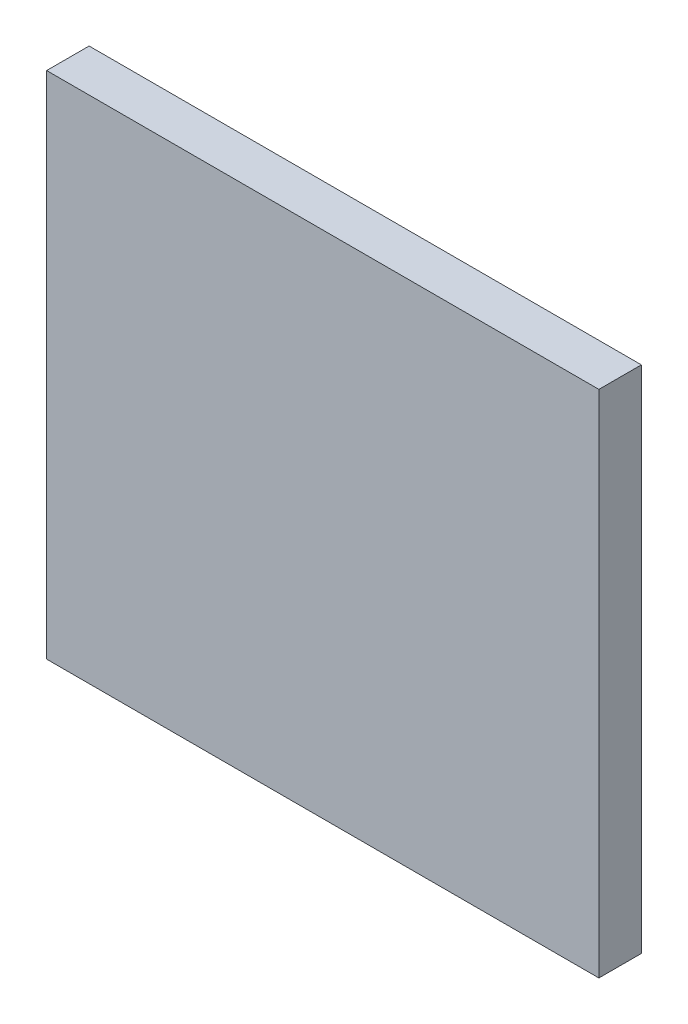
SolidWorks part; units mm, degrees
ref_plane "Front Plane" through (0, 0, 0) normal (0, 0, 1) x (1, 0, 0)
ref_plane "Top Plane" through (0, 0, 0) normal (0, 1, 0) x (1, 0, 0)
ref_plane "Right Plane" through (0, 0, 0) normal (1, 0, 0) x (0, 0, -1)
sketch "Sketch1" plane through (0, 0, 0) normal (0, 0, 1) x (1, 0, 0)
  line L1 (-59.1803, 36.2295) -> (5.8197, 36.2295)
  line L2 (-59.1803, 36.2295) -> (-59.1803, -23.7705)
  line L3 (-59.1803, -23.7705) -> (5.8197, -23.7705)
  line L4 (5.8197, 36.2295) -> (5.8197, -23.7705)
  dimension "D1" = 60
  dimension "D2" = 65
extrude "Boss-Extrude1" add sketch "Sketch1" along normal blind 5
